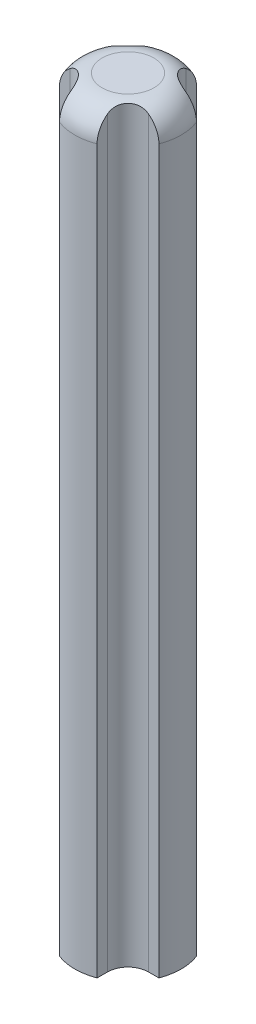
SolidWorks part; units mm, degrees
ref_plane "Front Plane" through (0, 0, 0) normal (0, 0, 1) x (1, 0, 0)
ref_plane "Top Plane" through (0, 0, 0) normal (0, 1, 0) x (1, 0, 0)
ref_plane "Right Plane" through (0, 0, 0) normal (1, 0, 0) x (0, 0, -1)
sketch "Sketch1" plane through (0, 0, 0) normal (0, 1, 0) x (1, 0, 0)
  circle A0 centre (0, 0) radius 3.9
  dimension "D1" = 7.8
extrude "Boss-Extrude1" add sketch "Sketch1" along normal blind 55
fillet "Fillet1" radius 2 1 edges at (0, 55, 3.9)
sketch "Sketch2" plane through (0, 55, 0) normal (0, 1, 0) x (1, 0, 0)
  line L0 (0, 0) -> (1.3789, -1.3789) construction
  line L1 (1.3789, -1.3789) -> (0, -1.3789) construction
  line L2 (1.3789, -1.3789) -> (3.8789, -1.3789)
  line L3 (1.3789, -1.3789) -> (1.3789, -3.8789)
  line L4 (1.3789, -3.8789) -> (3.8789, -3.8789)
  line L5 (3.8789, -1.3789) -> (3.8789, -3.8789)
  line L6 (0, -1.3789) -> (0, 0) construction
  dimension "D1" = 1.95
  dimension "D2" = 2.5
extrude "Cut-Extrude1" cut sketch "Sketch2" against normal through all
pattern_circular "CirPattern1" count 4 over 360 about axis through (0, 0, 0) along (0, 1, 0) of "Cut-Extrude1"
fillet "Fillet2" radius 1.5 4 edges at (1.3789, 27.4997, -1.3789) (-1.3789, 27.4997, -1.3789) (-1.3789, 27.4997, 1.3789) (1.3789, 27.4997, 1.3789)
